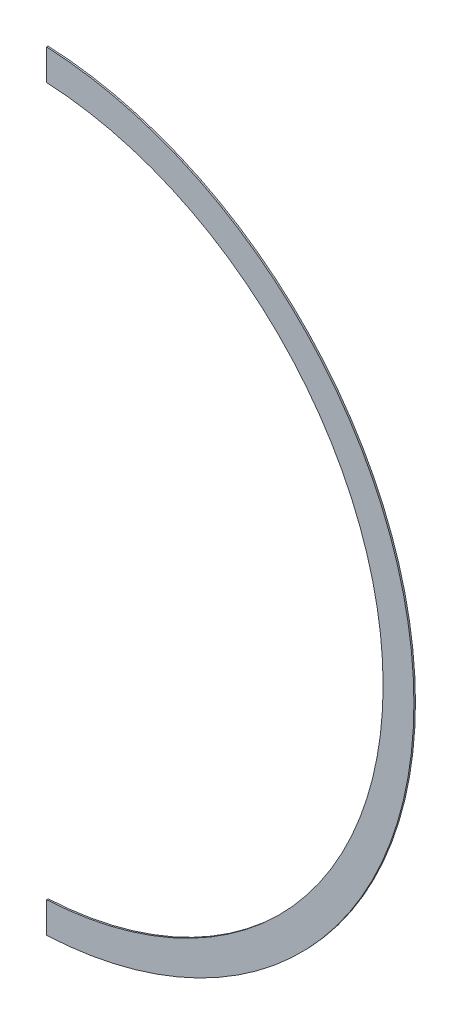
SolidWorks part; units mm, degrees
material "Galvanized Steel"
ref_plane "Front Plane" through (0, 0, 0) normal (0, 0, 1) x (1, 0, 0)
ref_plane "Top Plane" through (0, 0, 0) normal (0, 1, 0) x (1, 0, 0)
ref_plane "Right Plane" through (0, 0, 0) normal (1, 0, 0) x (0, 0, -1)
sketch "Sketch1" plane through (0, 0, 0) normal (0, 0, 1) x (1, 0, 0)
  line L0 (17.5, 339.5747) -> (17.5, 369.6074)
  line L1 (17.5, -379.5968) -> (17.5, -349.5622)
  line L4 (0, 509.726) -> (0, -798.5055) construction
  arc A4 (17.5, -349.5622) -> (17.5, 339.5747) centre (0.25, -4.9937) ccw
  arc A5 (17.5, -379.5968) -> (17.5, 369.6074) centre (0.2303, -4.9947) ccw
  point P6 (17.5, -364.5795)
  dimension "D1" = 35
  dimension "D3" = 375
  dimension "D4" = 345
  dimension "D2" = 17.5
  dimension "D5" = 30.0346
extrude "Boss-Extrude1" add sketch "Sketch1" along normal mid plane 1.5
